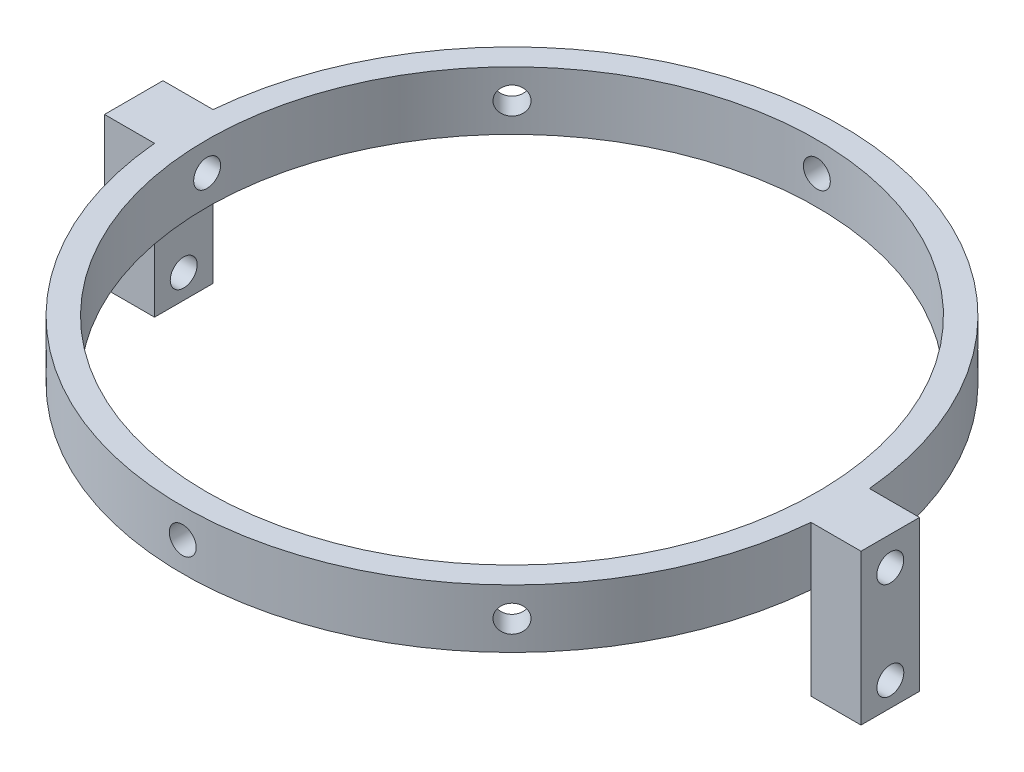
SolidWorks part; units mm, degrees
ref_plane "Front Plane" through (0, 0, 0) normal (0, 0, 1) x (1, 0, 0)
ref_plane "Top Plane" through (0, 0, 0) normal (0, 1, 0) x (1, 0, 0)
ref_plane "Right Plane" through (0, 0, 0) normal (1, 0, 0) x (0, 0, -1)
sketch "Sketch1" plane through (0, 0, 0) normal (0, 1, 0) x (1, 0, 0)
  line L0 (-167.7599, -127.506) -> (-167.7599, -119.886)
  line L2 (-69.2079, -119.886) -> (-75.7273, -119.886)
  line L3 (-69.2079, -119.886) -> (-69.2079, -127.506)
  line L4 (-69.2079, -127.506) -> (-75.7273, -127.506)
  line L5 (-167.7599, -119.886) -> (-161.2405, -119.886)
  line L7 (-167.7599, -127.506) -> (-161.2405, -127.506)
  circle A0 centre (-118.4839, -123.696) radius 39.751
  circle A2 centre (-118.4839, -123.696) radius 42.926
extrude "Boss-Extrude1" add sketch "Sketch1" along normal blind 7.62 contours A2 L5 L0 L7 | A2 A0 | A2 L4 L3 L2
sketch "Sketch2" plane through (0, 0, 0) normal (0, 0, 1) x (1, 0, 0)
  circle A0 centre (-118.4839, 3.81) radius 1.7526
extrude "Cut-Extrude1" cut sketch "Sketch2" along normal blind 95.7
pattern_circular "CirPattern1" count 8 over 360 about axis through (-118.4839, 7.62, 123.696) along (0, 1, 0) skipping 2, 6 of "Cut-Extrude1"
sketch "Sketch6" plane through (-167.7599, 0, 0) normal (-1, 0, 0) x (0, 0, 1)
  circle A0 centre (123.696, 3.8773) radius 1.7526
extrude "Cut-Extrude2" cut sketch "Sketch6" against normal blind 119.35
sketch "Sketch8" plane through (0, 7.62, 0) normal (0, 1, 0) x (1, 0, 0)
  line L1 (-69.2079, -127.506) -> (-75.7273, -127.506)
  line L2 (-69.2079, -127.506) -> (-69.2079, -119.886)
  line L3 (-69.2079, -119.886) -> (-75.7273, -119.886)
  line L4 (-75.7273, -127.506) -> (-75.7273, -119.886)
extrude "Boss-Extrude2" add sketch "Sketch8" against normal blind 12 from surface at -7.62 starting at face at (-118.4839, 0, 123.696)
sketch "Sketch9" plane through (-69.2079, 0, 0) normal (1, 0, 0) x (0, 0, -1)
  line L0 (-122.8087, 13.3092) -> (-123.696, -12)
  line L1 (-191.8909, 19.629) -> (-53.7265, 6.9893) construction
  line L2 (-127.506, -12) -> (-119.886, -12) construction
sketch "Sketch10" plane through (-69.2079, 0, 0) normal (1, 0, 0) x (0, 0, -1)
  circle A0 centre (-123.6839, -8.8496) radius 1.7526
extrude "Cut-Extrude3" cut sketch "Sketch10" against normal blind 9
pattern_circular "CirPattern2" count 2 over 360 about axis through (-118.4839, 7.62, 123.696) along (0, 1, 0) of "Boss-Extrude2", "Cut-Extrude3"
